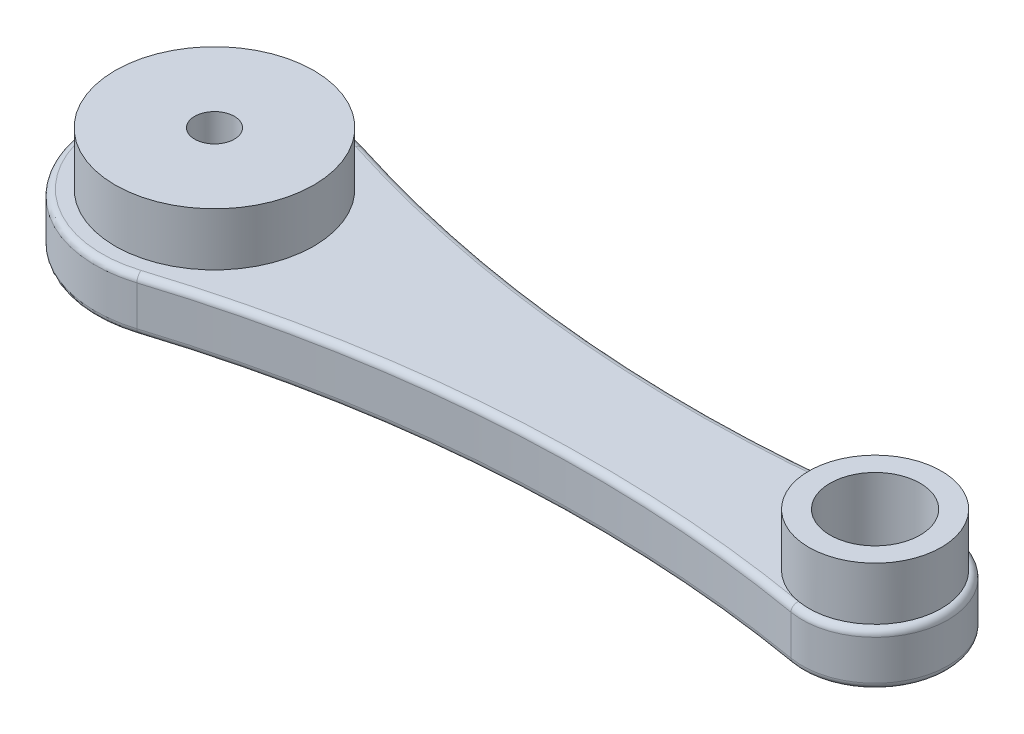
SolidWorks part; units mm, degrees
ref_plane "前视基准面" through (0, 0, 0) normal (0, 0, 1) x (1, 0, 0)
ref_plane "上视基准面" through (0, 0, 0) normal (0, 1, 0) x (1, 0, 0)
ref_plane "右视基准面" through (0, 0, 0) normal (1, 0, 0) x (0, 0, -1)
sketch "草图1" plane through (0, 0, 0) normal (0, 1, 0) x (1, 0, 0)
  line L0 (0, 0) -> (49.9, 0) construction
  circle A0 centre (0, 0) radius 1.5
  circle A1 centre (49.9, 0) radius 3.4
  arc A2 (2.7182, 8.5797) -> (2.7182, -8.5797) centre (0, 0) ccw
  arc A3 (48.9673, -5.4203) -> (48.9673, 5.4203) centre (49.9, 0) ccw
  arc A4 (2.7182, 8.5797) -> (48.9673, 5.4203) centre (32.3371, 102.0687) ccw
  arc A5 (2.7182, -8.5797) -> (48.9673, -5.4203) centre (32.3371, -102.0687) cw
  dimension "D1" = 18
  dimension "D2" = 11
  dimension "D3" = 6.8
  dimension "D4" = 3
  dimension "D5" = 45
  dimension "D6" = 8
extrude "凸台-拉伸1" add sketch "草图1" along normal blind 4
fillet "圆角1" radius 0.5 8 edges at (-9, 0, 0) (25.6534, 0, -4.228) (55.4, 0, 0) (-9, 4, 0) (25.6534, 4, -4.228) (55.4, 4, 0) (25.6534, 0, 4.228) (25.6534, 4, 4.228)
sketch "草图2" plane through (0, 4, 0) normal (0, 1, 0) x (1, 0, 0)
  circle A0 centre (0, 0) radius 7.5
  circle A1 centre (49.9, 0) radius 5
  circle A2 centre (49.9, 0) radius 3.4 construction
  circle A3 centre (0, 0) radius 1.5 construction
  circle A4 centre (49.9, 0) radius 3.4
  circle A5 centre (0, 0) radius 1.5
  dimension "D1" = 10
  dimension "D2" = 15
extrude "凸台-拉伸2" add sketch "草图2" along normal blind 4
